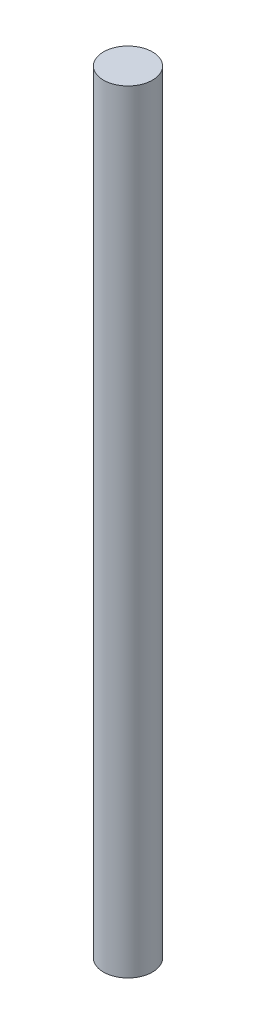
SolidWorks part; units mm, degrees
material "Alloy Steel"
ref_plane "Front Plane" through (0, 0, 0) normal (0, 0, 1) x (1, 0, 0)
ref_plane "Top Plane" through (0, 0, 0) normal (0, 1, 0) x (1, 0, 0)
ref_plane "Right Plane" through (0, 0, 0) normal (1, 0, 0) x (0, 0, -1)
sketch "Sketch1" plane through (0, 0, 0) normal (0, 1, 0) x (1, 0, 0)
  circle A0 centre (0, 0) radius 4
  dimension "D1" = 8
extrude "Boss-Extrude1" add sketch "Sketch1" along normal blind 126.2
equation "\"____ GENERATED PART EXPORTS ____\" = 0"
equation "\"SYS_VersionTag\" = 2"
equation "\"SFT_ShaftDiameter\" = 8mm"
equation "\"SFT_FixedShaftCutLength\" = 126.2mm"
equation "\"D1@Sketch1\"=\"SFT_ShaftDiameter\""
equation "\"D1@Boss-Extrude1\"=\"SFT_FixedShaftCutLength\""
